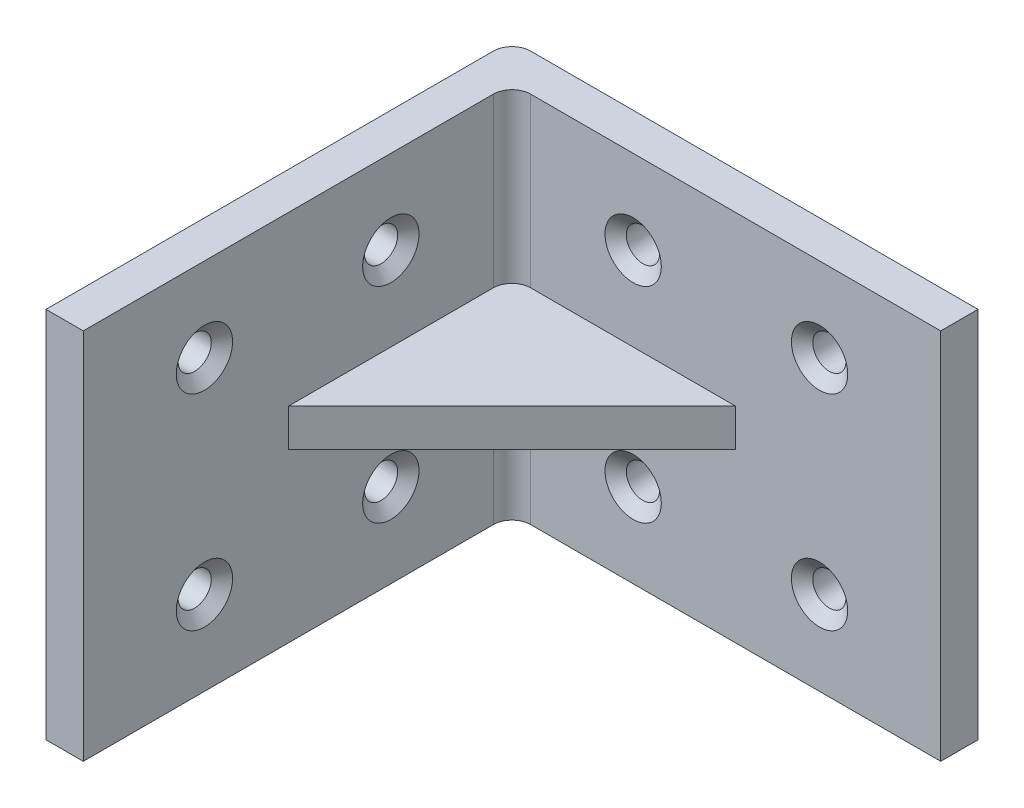
SolidWorks part; units mm, degrees
ref_plane "Front Plane" through (0, 0, 0) normal (0, 0, 1) x (1, 0, 0)
ref_plane "Top Plane" through (0, 0, 0) normal (0, 1, 0) x (1, 0, 0)
ref_plane "Right Plane" through (0, 0, 0) normal (1, 0, 0) x (0, 0, -1)
sketch "Sketch1" plane through (0, 0, 0) normal (0, 0, 1) x (1, 0, 0)
  line L1 (-63.9, 9.8824) -> (-88.9, 9.8824)
  line L2 (-63.9, 9.8824) -> (-63.9, 29.8824)
  line L3 (-63.9, 29.8824) -> (-88.9, 29.8824)
  line L4 (-88.9, 9.8824) -> (-88.9, 29.8824)
  dimension "D1" = 20
  dimension "D2" = 25
extrude "Boss-Extrude1" add sketch "Sketch1" along normal blind 2 contours L1 L4 L3 L2
sketch "Sketch2" plane through (0, 0, 2) normal (0, 0, 1) x (1, 0, 0)
  line L0 (-63.9, 9.8824) -> (-88.9, 9.8824) construction
  line L1 (-88.9, 29.8824) -> (-86.9, 29.8824)
  line L2 (-88.9, 29.8824) -> (-88.9, 9.8824)
  line L3 (-88.9, 9.8824) -> (-86.9, 9.8824)
  line L4 (-86.9, 29.8824) -> (-86.9, 9.8824)
  dimension "D1" = 2
extrude "Boss-Extrude2" add sketch "Sketch2" along normal blind 23
fillet "Fillet2" radius 1 1 edges
fillet "Fillet3" radius 1 1 edges at (-88.9, 19.8824, 0)
ref_plane "Plane1" through (0, 19.8824, 0) normal (0, -1, 0) x (-1, 0, 0)
sketch "Sketch4" plane through (0, 19.8824, 0) normal (0, -1, 0) x (-1, 0, 0)
  line L0 (86.9, -14) -> (74.9, -2)
  line L1 (86.9, -25) -> (86.9, -3) construction
  line L2 (63.9, -2) -> (85.9, -2) construction
rib "Rib1" sketch "Sketch4" sketch "Sketch4" thickness 2 extrusion direction parallel to sketch draft on no parameters "D1"=2
hole_wizard "CSK for #0 Flat Head Machine Screw (100)1" positions "Sketch6" profile "Sketch5" countersink size "#0" standard "ANSI Inch"
sketch "Sketch6" plane through (0, 0, 2) normal (0, 0, 1) x (1, 0, 0)
  point P0 (-80.4, 14.3824)
  point P2 (-70.4, 14.3824)
  dimension "D1" = 10
sketch "Sketch5" plane through (-80.4, 14.3824, 2) normal (1, 0, 0) x (0, -1, 0)
  line L0 (0, 0) -> (0, 10.5342)
  line L1 (0, 10.5342) -> (0.889, 10)
  line L2 (0.889, 10) -> (0.889, 0.5222)
  line L3 (0.889, 0.5222) -> (1.5113, 0)
  line L5 (1.5113, 0) -> (0, 0)
  line L6 (-0.889, 0.5222) -> (-1.5113, 0) construction
  line L10 (0, 10.5342) -> (-0.889, 10) construction
  line L11 (0, -6.35) -> (0, 107.95) construction
  dimension "Hole Dia." = 1.778
  dimension "Hole Depth" = 10
  dimension "Near C'Sink Dia." = 3.0226
  dimension "Near C'Sink Angle" = 100
  dimension "Drill Angle" = 118
sketch "Sketch7" plane through (0, 0, 2) normal (0, 0, 1) x (1, 0, 0)
  line L0 (-63.9, 19.7195) -> (-74.9, 19.8824) construction
  line L1 (-63.9, 9.8824) -> (-63.9, 29.8824) construction
  line L2 (-74.9, 18.8824) -> (-74.9, 20.8824) construction
sketch "Sketch8" plane through (0, 18.8824, 0) normal (0, -1, 0) x (-1, 0, 0)
  line L0 (80.9, -8) -> (86.6071, -2.2929) construction
  line L1 (86.9, -14) -> (74.9, -2) construction
  arc A0 (86.9, -3) -> (85.9, -2) centre (85.9, -3) ccw construction
ref_plane "Plane2" through (0, 19.8824, 0) normal (0, -1, 0) x (-1, 0, 0)
mirror "Mirror1" about plane through (0, 19.8824, 0) normal (0, -1, 0) of "CSK for #0 Flat Head Machine Screw (100)1"
sketch "Sketch9" plane through (-36.45, 0, -36.45) normal (0.7071, 0, 0.7071) x (0.7071, 0, -0.7071)
  line L0 (-62.8618, 18.8824) -> (-62.8618, 20.8824) construction
  line L1 (-71.3471, 18.8824) -> (-54.3765, 18.8824) construction
  line L2 (-71.3471, 20.8824) -> (-54.3765, 20.8824) construction
ref_plane "Plane3" through (-44.45, 0, 44.45) normal (0.7071, 0, -0.7071) x (-0.7071, 0, -0.7071)
mirror "Mirror2" about plane through (-44.45, 0, 44.45) normal (0.7071, 0, -0.7071) of "Mirror1", "CSK for #0 Flat Head Machine Screw (100)1"
